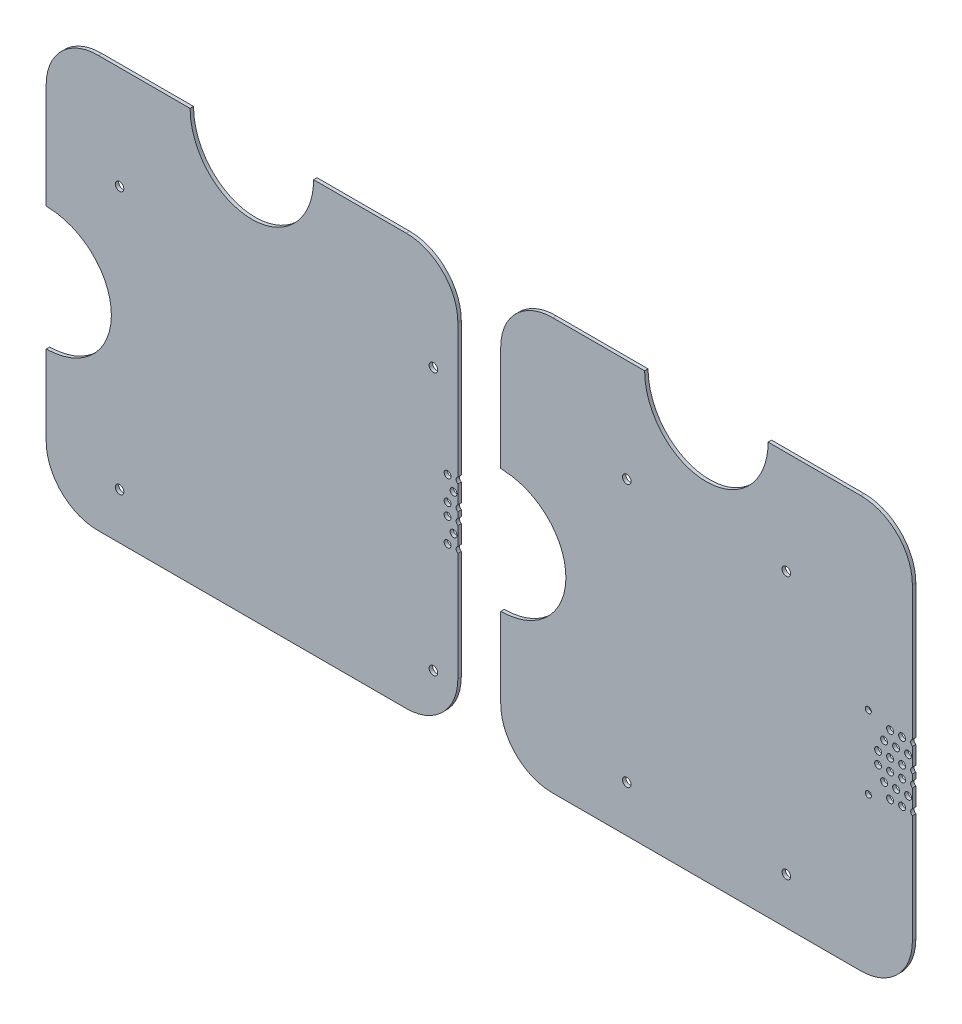
SolidWorks part; units mm, degrees
ref_plane "Front Plane" through (0, 0, 0) normal (0, 0, 1) x (1, 0, 0)
ref_plane "Top Plane" through (0, 0, 0) normal (0, 1, 0) x (1, 0, 0)
ref_plane "Right Plane" through (0, 0, 0) normal (1, 0, 0) x (0, 0, -1)
sketch "Sketch1" plane through (0, 0, 0) normal (0, 0, 1) x (1, 0, 0)
  line L0 (436.5465, 30.9688) -> (436.5465, -197.6312)
  line L1 (131.7465, 30.9688) -> (131.7465, -46.865)
  line L2 (131.7465, -138.4809) -> (131.7465, -197.6312)
  line L3 (169.8465, -235.7312) -> (398.4465, -235.7312)
  line L4 (436.5465, -197.6312) -> (436.5465, -138.3929)
  line L5 (436.5465, -46.9529) -> (436.5465, 30.9688)
  line L6 (131.7465, -46.865) -> (131.7465, -138.4809)
  line L7 (238.2898, 69.0688) -> (329.7784, 69.0688)
  line L8 (773.093, 30.9688) -> (773.093, -197.6312)
  line L9 (773.093, -197.6312) -> (772.7871, -197.492)
  line L10 (468.293, 30.9688) -> (468.293, -197.6312)
  line L11 (574.8362, 69.0688) -> (666.2762, 69.0688)
  line L12 (506.96, 69.0646) -> (734.993, 69.0688)
  line L14 (238.2898, 69.0688) -> (170.4136, 69.0646)
  line L15 (398.4465, 69.0688) -> (329.7784, 69.0688)
  line L27 (468.293, 30.9688) -> (468.293, -46.865)
  line L28 (468.293, -138.4809) -> (468.293, -197.6312)
  line L29 (506.393, -235.7312) -> (734.993, -235.7312)
  line L42 (574.8362, 69.0688) -> (506.96, 69.0646)
  line L43 (734.993, 69.0688) -> (666.3249, 69.0688)
  arc A0 (131.7465, 30.9688) -> (170.4136, 69.0646) centre (169.8465, 30.9688) cw
  arc A1 (169.8465, -235.7312) -> (131.7465, -197.6312) centre (169.8465, -197.6312) cw
  arc A2 (436.5465, -197.6312) -> (398.4465, -235.7312) centre (398.4465, -197.6312) cw
  arc A3 (436.5465, 30.9688) -> (398.4465, 69.0688) centre (398.4465, 30.9688) ccw
  circle A8 centre (186.0517, -7.055) radius 3.175
  circle A9 centre (418.4617, -7.055) radius 3.175
  circle A10 centre (418.4617, -201.365) radius 3.175
  circle A11 centre (186.0517, -201.365) radius 3.175
  arc A12 (468.293, 30.9688) -> (506.96, 69.0646) centre (506.393, 30.9688) cw
  arc A13 (506.393, -235.7312) -> (468.293, -197.6312) centre (506.393, -197.6312) cw
  arc A14 (773.093, -197.6312) -> (734.993, -235.7312) centre (734.993, -197.6312) cw
  arc A15 (773.093, 30.9688) -> (734.993, 69.0688) centre (734.993, 30.9688) ccw
  circle A20 centre (561.638, -7.055) radius 3.175
  circle A21 centre (561.638, -201.365) radius 3.175
  circle A22 centre (679.748, -201.365) radius 3.175
  circle A23 centre (679.748, -7.055) radius 3.175
  circle A68 centre (433.3715, -106.0079) radius 2.54
  circle A71 centre (428.9265, -97.1179) radius 2.54
  arc A73 (436.5465, -94.9182) -> (436.5465, -99.3177) centre (437.8165, -97.1179) ccw
  arc A74 (436.5465, -90.4277) -> (436.5465, -86.0282) centre (437.8165, -88.2279) cw
  circle A76 centre (428.9265, -88.2279) radius 2.54
  circle A79 centre (433.3715, -79.3379) radius 2.54
  arc A85 (436.5465, -72.6477) -> (436.5465, -68.2482) centre (437.8165, -70.4479) cw
  circle A87 centre (428.9265, -70.4479) radius 2.54
  arc A88 (436.5465, -117.0977) -> (436.5465, -112.6982) centre (437.8165, -114.8979) cw
  circle A90 centre (428.9265, -114.8979) radius 2.54
  circle A125 centre (756.583, -114.8979) radius 2.54
  circle A128 centre (765.473, -97.1179) radius 2.54
  circle A129 centre (747.693, -88.2279) radius 2.54
  circle A131 centre (747.693, -97.1179) radius 2.54
  arc A132 (773.093, -90.4277) -> (773.093, -86.0282) centre (774.363, -88.2279) cw
  circle A134 centre (752.138, -79.3379) radius 2.54
  arc A135 (773.093, -94.9182) -> (773.093, -99.3177) centre (774.363, -97.1179) ccw
  arc A136 (773.093, -72.6477) -> (773.093, -68.2482) centre (774.363, -70.4479) cw
  circle A137 centre (769.918, -106.0079) radius 2.54
  circle A138 centre (761.028, -79.3379) radius 2.54
  circle A139 centre (740.4752, -65.6447) radius 2.2479
  circle A140 centre (761.028, -106.0079) radius 2.54
  circle A143 centre (769.918, -79.3379) radius 2.54
  arc A144 (773.093, -117.0977) -> (773.093, -112.6982) centre (774.363, -114.8979) cw
  circle A146 centre (756.583, -97.1179) radius 2.54
  circle A150 centre (765.473, -70.4479) radius 2.54
  circle A151 centre (756.583, -70.4479) radius 2.54
  circle A152 centre (752.138, -106.0079) radius 2.54
  circle A153 centre (756.583, -88.2279) radius 2.54
  circle A155 centre (765.473, -88.2279) radius 2.54
  circle A156 centre (765.473, -114.8979) radius 2.54
  circle A157 centre (740.4752, -119.7011) radius 2.2479
  ellipse E0 centre (284.0098, 69.0688) end of major axis (284.0098, 117.3288) minor radius 45.72 (238.2898, 69.0688) -> (329.7298, 69.0688) ccw
  ellipse E1 centre (620.5562, 69.0688) end of major axis (620.5562, 20.8088) minor radius 45.72 (574.8362, 69.0688) -> (666.2762, 69.0688) ccw
  spline S4 degree 3 poles (468.293, -46.865) (469.1265, -46.914) (470.1691, -46.9763) (471.4181, -47.048) (472.1904, -47.0996) (473.5693, -47.2165) (475.5201, -47.4507) (478.6298, -47.9707) (482.4552, -48.889) (488.3899, -50.9167) (495.3579, -54.4734) (502.6995, -60.1927) (508.7068, -67.1599) (514.677, -77.7474) (517.8036, -92.6729) (514.677, -107.5985) (508.7068, -118.1859) (502.6995, -125.1532) (495.3579, -130.8725) (488.3899, -134.4292) (482.4552, -136.4569) (478.6298, -137.3752) (475.5201, -137.8952) (473.5693, -138.1294) (472.1904, -138.2463) (471.4181, -138.2979) (470.1691, -138.3696) (469.1265, -138.4319) (468.293, -138.4809) knots 1.574224 1.574224 1.574224 1.574224 1.623204 1.635449 1.647694 1.672184 1.721165 1.770145 1.868105 1.966066 2.161987 2.357908 2.553829 2.74975 3.141593 3.533435 3.729356 3.925277 4.121198 4.317119 4.41508 4.51304 4.562021 4.611001 4.635491 4.647736 4.659981 4.708962 4.708962 4.708962 4.708962
  spline S5 degree 3 poles (131.7465, -46.865) (132.58, -46.914) (133.6226, -46.9763) (134.8717, -47.048) (135.644, -47.0996) (137.0229, -47.2165) (138.9737, -47.4507) (142.0834, -47.9707) (145.9088, -48.889) (151.8434, -50.9167) (158.8114, -54.4734) (166.153, -60.1927) (172.1603, -67.1599) (178.1305, -77.7474) (181.2572, -92.6729) (178.1305, -107.5985) (172.1603, -118.1859) (166.153, -125.1532) (158.8114, -130.8725) (151.8434, -134.4292) (145.9088, -136.4569) (142.0834, -137.3752) (138.9737, -137.8952) (137.0229, -138.1294) (135.644, -138.2463) (134.8717, -138.2979) (133.6226, -138.3696) (132.58, -138.4319) (131.7465, -138.4809) knots 1.574224 1.574224 1.574224 1.574224 1.623204 1.635449 1.647694 1.672184 1.721165 1.770145 1.868105 1.966066 2.161987 2.357908 2.553829 2.74975 3.141593 3.533435 3.729356 3.925277 4.121198 4.317119 4.41508 4.51304 4.562021 4.611001 4.635491 4.647736 4.659981 4.708962 4.708962 4.708962 4.708962
extrude "Boss-Extrude1" add sketch "Sketch1" along normal blind 2.54
